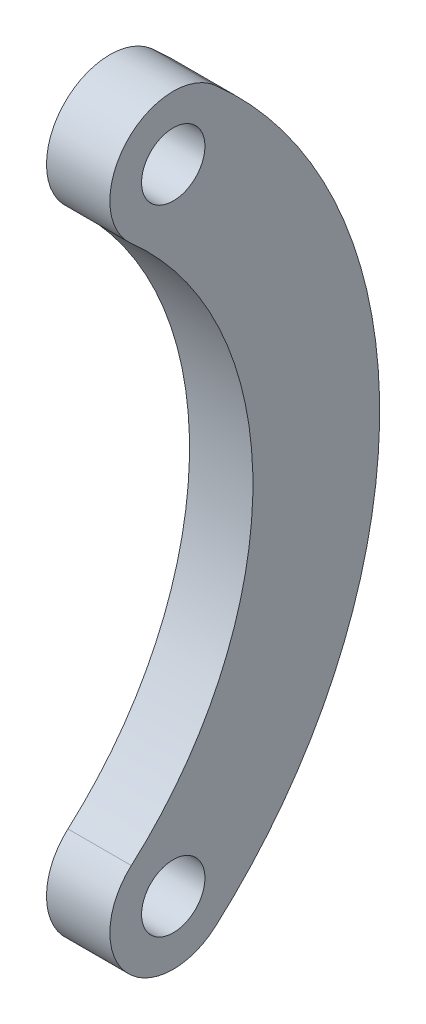
SolidWorks part; units mm, degrees
ref_plane "Front Plane" through (0, 0, 0) normal (1, 0, 0) x (0, 1, 0)
ref_plane "Top Plane" through (0, 0, 0) normal (0, 0, 1) x (0, 1, 0)
ref_plane "Right Plane" through (0, 0, 0) normal (0, 1, 0) x (-1, 0, 0)
sketch "Sketch1" plane through (0, 0, 0) normal (1, 0, 0) x (0, 1, 0)
  line L0 (0, -127) -> (0, 0) construction
  arc A0 (-95.25, -84.0026) -> (0, -127) centre (0, 0) ccw construction
  circle A1 centre (-95.25, -84.0026) radius 9.525
  arc A2 (80.9625, -71.4022) -> (-80.9625, -71.4022) centre (0, 0) cw
  arc A3 (109.5375, -96.603) -> (-109.5375, -96.603) centre (0, 0) cw
  arc A4 (-109.5375, -96.603) -> (-80.9625, -71.4022) centre (-95.25, -84.0026) cw
  arc A5 (109.5375, -96.603) -> (80.9625, -71.4022) centre (95.25, -84.0026) ccw
  circle A6 centre (95.25, -84.0026) radius 9.525
  point P10 (-8.9114, -145.7779)
  point P11 (-93.7069, -85.7206)
  dimension "D2" = 19.05
  dimension "D4" = 19.05
  dimension "D1" = 127
  dimension "D3" = 190.5
extrude "Boss-Extrude1" add sketch "Sketch1" along normal blind 19.05 contours A3 A5 A2 A4 A1 A6
